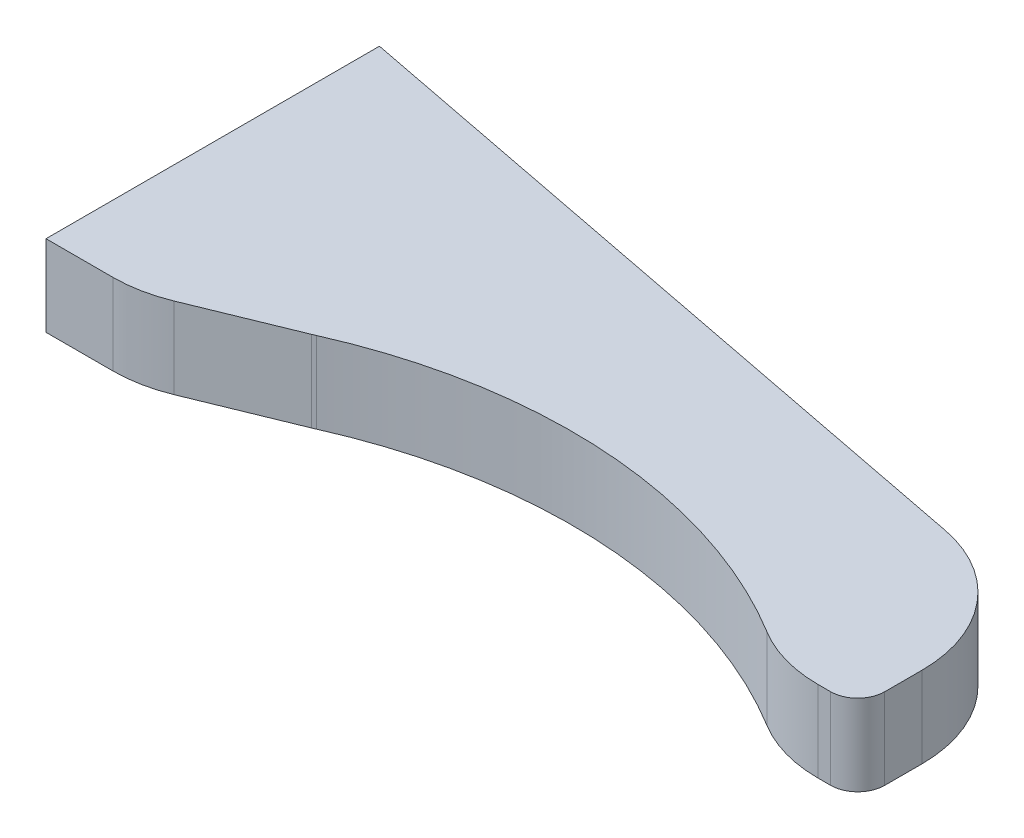
SolidWorks part; units mm, degrees
ref_plane "Front Plane" through (0, 0, 0) normal (0, 0, 1) x (1, 0, 0)
ref_plane "Top Plane" through (0, 0, 0) normal (0, 1, 0) x (1, 0, 0)
ref_plane "Right Plane" through (0, 0, 0) normal (1, 0, 0) x (0, 0, -1)
sketch "Sketch1" plane through (0, 0, 0) normal (0, 1, 0) x (1, 0, 0)
  line L1 (20, -6.5) -> (-20, -6.5)
  line L2 (20, -6.5) -> (20, 6.5)
  line L3 (20, 6.5) -> (-20, 6.5)
  line L4 (-20, -6.5) -> (-20, 6.5)
  line L5 (20, -6.5) -> (-20, 6.5) construction
  line L6 (20, 6.5) -> (-20, -6.5) construction
  point P0 (0, 0)
  dimension "D1" = 13
  dimension "D2" = 40
extrude "Boss-Extrude1" add sketch "Sketch1" along normal blind 3
sketch "Sketch3" plane through (0, 3, 0) normal (0, 1, 0) x (1, 0, 0)
  line L0 (-20, 6.5) -> (-20, -6.5) construction
  line L1 (20, 6.5) -> (-20, 6.5) construction
  circle A0 centre (-17, 4) radius 1.25
  circle A1 centre (-17, -4) radius 1.25
  dimension "D1" = 2.5
  dimension "D3" = 2.5
  dimension "D4" = 2.5
  dimension "D5" = 8
  dimension "D2" = 3
extrude "Cut-Extrude2" cut sketch "Sketch3" against normal through all
sketch "Sketch5" plane through (0, 3, 0) normal (0, 1, 0) x (1, 0, 0)
  line L0 (-13.4582, 6.5) -> (20, 0)
  line L2 (20, 6.5) -> (-20, 6.5) construction
  line L3 (20, -6.5) -> (20, 6.5) construction
  line L4 (20, 0) -> (20, -6.5)
  line L5 (20, -6.5) -> (17.0301, -6.5)
  line L6 (-20, -6.5) -> (20, -6.5) construction
  line L7 (-1.9773, -4.6243) -> (-6.5697, -6.5)
  line L8 (-6.5697, -6.5) -> (-13.4582, -6.5)
  line L9 (-13.4582, -6.5) -> (-13.4582, -10.2372)
  line L10 (-13.4582, -10.2372) -> (26.0235, -9.7269)
  line L11 (26.0235, -9.7269) -> (26.0235, 8.4773)
  line L12 (26.0235, 8.4773) -> (-13.4582, 8.4773)
  line L13 (-13.4582, 8.4773) -> (-13.4582, 6.5)
  arc A0 (17.0301, -6.5) -> (-1.9773, -4.6243) centre (5.8843, -22.2017) ccw
extrude "Cut-Extrude3" cut sketch "Sketch5" against normal blind 10
fillet "Fillet2" radius 5 3 edges at (17.0301, 1.5, 6.5) (-1.9773, 1.5, 4.6243) (-6.5697, 1.5, 6.5)
fillet "Fillet3" radius 1 1 edges at (20, 1.5, 6.5)
fillet "Fillet4" radius 5 1 edges at (20, 1.5, 0)
fillet "Fillet5" radius 5 1 edges at (-13.4582, 1.5, -6.5)
sketch "Sketch6" plane through (0, 3, 0) normal (0, 1, 0) x (1, 0, 0)
  line L1 (-10.0207, 12.8794) -> (-25.2383, 12.8794)
  line L2 (-10.0207, 12.8794) -> (-10.0207, -14.2587)
  line L3 (-10.0207, -14.2587) -> (-25.2383, -14.2587)
  line L4 (-25.2383, 12.8794) -> (-25.2383, -14.2587)
extrude "Cut-Extrude5" cut sketch "Sketch6" against normal blind 10
